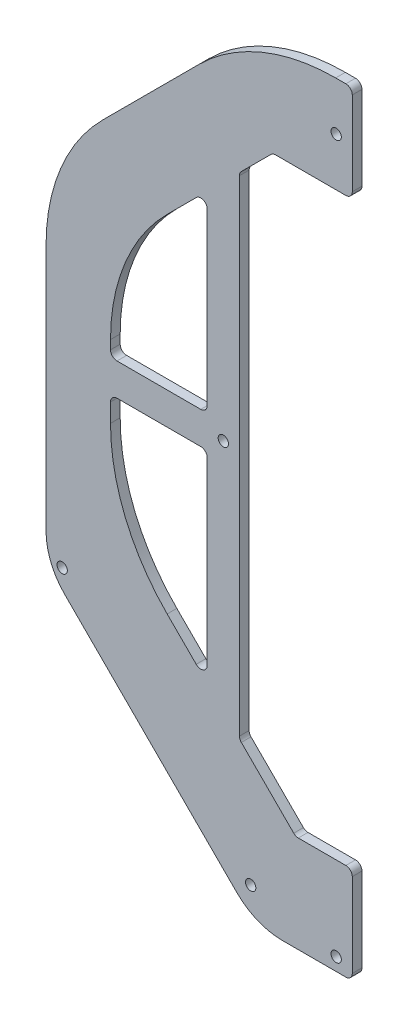
SolidWorks part; units mm, degrees
ref_plane "Front Plane" through (0, 0, 0) normal (0, 0, 1) x (1, 0, 0)
ref_plane "Top Plane" through (0, 0, 0) normal (0, 1, 0) x (1, 0, 0)
ref_plane "Right Plane" through (0, 0, 0) normal (1, 0, 0) x (0, 0, -1)
sketch "ｽｹｯﾁ1" plane through (0, 0, 0) normal (0, 0, 1) x (1, 0, 0)
  line L0 (0, 0) -> (-30, 0)
  line L1 (-30, 0) -> (-95, 65)
  line L2 (-95, 65) -> (-95, 175)
  line L3 (-95, 175) -> (-30, 240)
  line L4 (-30, 240) -> (0, 240)
  line L5 (0, 240) -> (0, 210)
  line L6 (0, 210) -> (-24.6447, 210)
  line L7 (-24.6447, 210) -> (-75, 159.6447)
  line L8 (-75, 159.6447) -> (-75, 87.4264)
  line L9 (-75, 87.4264) -> (-17.5736, 30)
  line L10 (-17.5736, 30) -> (0, 30)
  line L11 (0, 30) -> (0, 0)
  line L12 (-45, 189.6447) -> (-45, 57.4264)
  line L13 (-35, 199.6447) -> (-35, 47.4264)
  line L19 (-45, 130.0355) -> (-75, 130.0355)
  line L20 (-45, 130.0355) -> (-45, 120.0355)
  line L21 (-45, 120.0355) -> (-75, 120.0355)
  line L22 (-75, 130.0355) -> (-75, 120.0355)
  circle A0 centre (-40, 125.0355) radius 1.6
  circle A1 centre (-5, 4) radius 1.6
  circle A2 centre (-31.5147, 10) radius 1.6
  circle A3 centre (-5, 225) radius 1.6
  circle A4 centre (-90, 66) radius 1.6
  point P19 (-75, 123.5355)
  dimension "D13" = 3.2
  dimension "D14" = 4
  dimension "D15" = 5
  dimension "D16" = 3.2
  dimension "D17" = 6
  dimension "D18" = 10
  dimension "D19" = 3.2
  dimension "D21" = 5
  dimension "D24" = 3.2
  dimension "D25" = 5
  dimension "D26" = 15
  dimension "D27" = 3.2
  dimension "D28" = 5
  dimension "D29" = 1
  dimension "D30" = 5
  dimension "D1" = 30
  dimension "D2" = 240
  dimension "D3" = 0
  dimension "D4" = 95
  dimension "D5" = 20
  dimension "D6" = 135
  dimension "D7" = 135
  dimension "D8" = 25
  dimension "D9" = 30
  dimension "D10" = 65
  dimension "D11" = 65
  dimension "D12" = 30
  dimension "D20" = 1.5
  dimension "D22" = 10
  dimension "D23" = 35
  dimension "D31" = 5
extrude "ﾎﾞｽ - 押し出し1" add sketch "ｽｹｯﾁ1" along normal blind 3 contours L11 L10 L9 L8 L7 L6 L5 L4 L3 L2 L1 L0 A2 A1 | L13 L7 L12 L9 A0 | L21 L12 L19 L8
fillet "ﾌｨﾚｯﾄ1" radius 60 4 edges at (-75, 159.6447, 1.5) (-95, 175, 1.5) (-30, 240, 1.5) (-75, 87.4264, 1.5)
fillet "ﾌｨﾚｯﾄ2" radius 2 8 edges at (0, 0, 1.5) (0, 30, 1.5) (-35, 47.4264, 1.5) (-17.5736, 30, 1.5) (-35, 199.6447, 1.5) (-24.6447, 210, 1.5) (0, 210, 1.5) (0, 240, 1.5)
fillet "ﾌｨﾚｯﾄ3" radius 20 2 edges at (-30, 0, 1.5) (-95, 65, 1.5)
fillet "ﾌｨﾚｯﾄ4" radius 2 6 edges at (-45, 189.6447, 1.5) (-75, 130.0355, 1.5) (-45, 130.0355, 1.5) (-75, 120.0355, 1.5) (-45, 57.4264, 1.5) (-45, 120.0355, 1.5)
